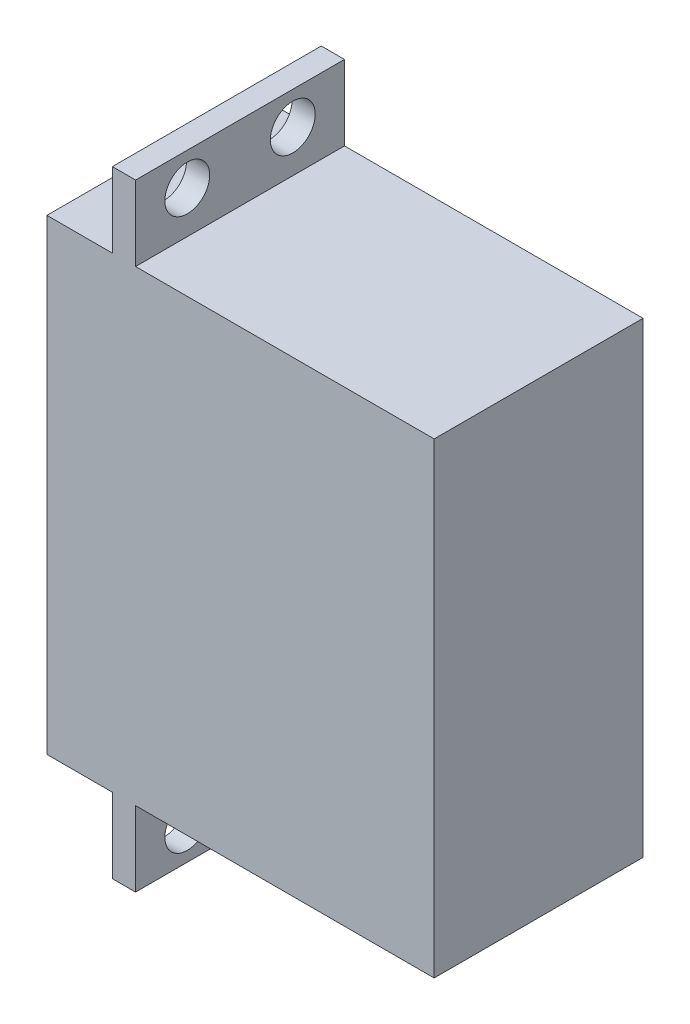
SolidWorks part; units mm, degrees
ref_plane "Piano frontale" through (0, 0, 0) normal (0, 0, 1) x (1, 0, 0)
ref_plane "Piano superiore" through (0, 0, 0) normal (0, 1, 0) x (1, 0, 0)
ref_plane "Piano destro" through (0, 0, 0) normal (1, 0, 0) x (0, 0, -1)
sketch "Schizzo1" plane through (0, 0, 0) normal (0, 0, 1) x (-1, 0, 0)
  line L0 (0, 106) -> (0, 74) construction
  line L1 (68, 16.5) -> (-54.1, 16.5) construction
  line L2 (106, 0) -> (68, 0) construction
  line L3 (0, 74) -> (68, 74) construction
  line L4 (68, 74) -> (68, -41)
  line L5 (68, -41) -> (-97.7497, -41)
  line L6 (68, 74) -> (-75.8947, 74)
  line L7 (-54.1, -983.5) -> (-54.1, 49016.5) construction
  line L8 (32.3, -100.959) -> (32.3, -50.959)
  line L9 (-54.1, 16.5) -> (-54.1, -23.5) construction
  line L10 (32.3, -50.959) -> (-32.3, -50.959)
  line L11 (-54.1, -23.5) -> (-59.1, -23.5) construction
  line L12 (-32.3, -50.959) -> (-32.3, -100.959)
  line L14 (-59.1, -23.5) -> (-99.4, -23.5)
  line L15 (-59.1, -23.5) -> (-59.1, 20.75)
  line L16 (-59.1, 20.75) -> (-99.4, 20.75)
  line L17 (-99.4, -23.5) -> (-99.4, 20.75)
  arc A2 (32.3, -100.959) -> (-32.3, -100.959) centre (0, 0) ccw
  point P22 (0, 0)
  point P23 (0, 0)
  point P24 (0, 0)
  point P25 (0, 0)
  point P26 (0, 0)
  point P27 (0, 0)
  point P28 (0, 0)
  point P29 (0, 0)
extrude "Estrusione-Estrusione1" add sketch "Schizzo1" along normal blind 19.8 contours L15 L14 L17 L16
sketch "Schizzo2" plane through (59.1, 0, 0) normal (-1, 0, 0) x (0, 0, 1)
  line L0 (0, 23.5) -> (9.9, 23.5)
  line L1 (0, -20.75) -> (19.8, -20.75)
  line L2 (0, -20.75) -> (0, 23.5)
  line L3 (0, 23.5) -> (19.8, 23.5)
  line L4 (19.8, -20.75) -> (19.8, 23.5)
  line L5 (9.9, 23.5) -> (9.9, 12.5) construction
  circle A0 centre (9.9, 12.5) radius 2.9
extrude "Taglio-Estrusione1" cut sketch "Schizzo2" against normal blind 3.6
sketch "Schizzo3" plane through (0, 23.5, 0) normal (0, 1, 0) x (1, 0, 0)
  line L0 (99.4, 0) -> (71.1, 0) construction
  line L1 (62.7, 0) -> (99.4, 0) construction
  line L2 (62.7, -19.8) -> (99.4, -19.8) construction
  line L3 (71.1, 0) -> (68.9, 0)
  line L4 (71.1, 0) -> (71.1, -19.8)
  line L5 (71.1, -19.8) -> (68.9, -19.8)
  line L6 (68.9, 0) -> (68.9, -19.8)
  point P10 (0, 0)
extrude "Estrusione-Estrusione2" add sketch "Schizzo3" along normal blind 7.1
sketch "Schizzo4" plane through (0, -20.75, 0) normal (0, -1, 0) x (1, 0, 0)
  line L0 (99.4, 19.8) -> (71.1, 19.8) construction
  line L1 (62.7, 19.8) -> (99.4, 19.8) construction
  line L2 (62.7, 0) -> (99.4, 0) construction
  line L3 (71.1, 19.8) -> (68.9, 19.8)
  line L4 (71.1, 19.8) -> (71.1, 0)
  line L5 (71.1, 0) -> (68.9, 0)
  line L6 (68.9, 19.8) -> (68.9, 0)
  point P10 (0, 0)
extrude "Estrusione-Estrusione3" add sketch "Schizzo4" along normal blind 7.1
sketch "Schizzo5" plane through (68.9, 0, 0) normal (-1, 0, 0) x (0, 0, 1)
  line L0 (9.9, -983.956) -> (9.9, 49016.044) construction
  line L1 (9.9, 12.5) -> (9.9, 27.5) construction
  line L2 (9.9, 27.5) -> (14.9, 27.5) construction
  line L3 (-1000, 1.375) -> (49000, 1.375) construction
  line L4 (0, 23.5) -> (0, -20.75) construction
  circle A1 centre (14.9, 27.5) radius 2.125
  circle A2 centre (4.9, 27.5) radius 2.125
  circle A3 centre (14.9, -24.75) radius 2.125
  circle A4 centre (4.9, -24.75) radius 2.125
  point P15 (0, 1.375)
extrude "Taglio-Estrusione2" cut sketch "Schizzo5" against normal blind 7.1
